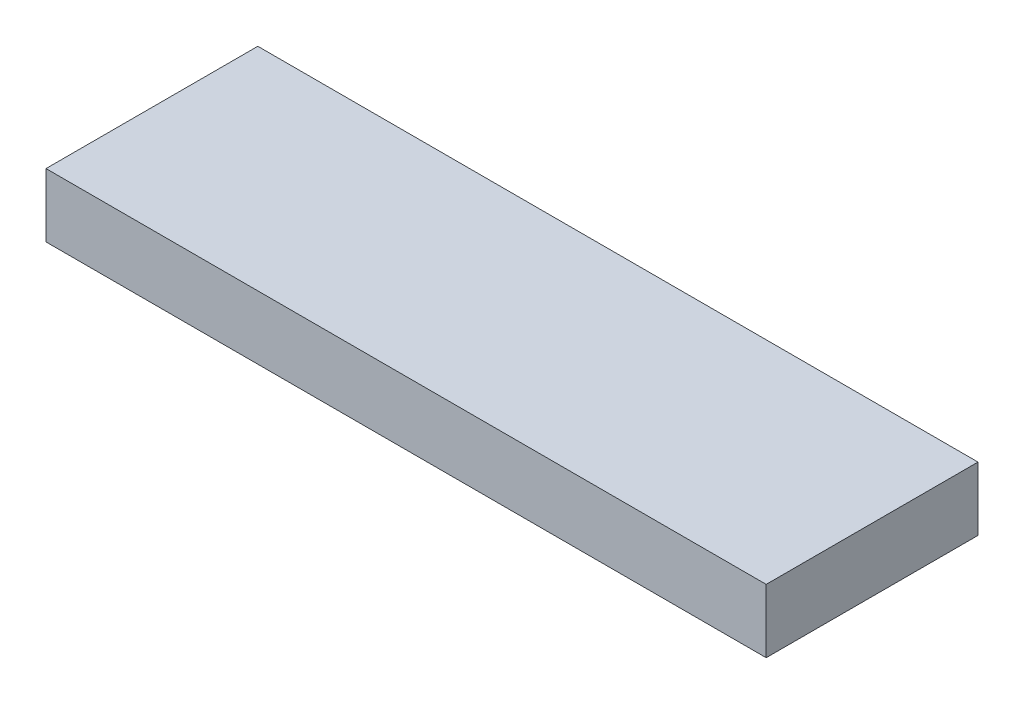
SolidWorks part; units mm, degrees
ref_plane "前视基准面" through (0, 0, 0) normal (0, 0, 1) x (1, 0, 0)
ref_plane "上视基准面" through (0, 0, 0) normal (0, 1, 0) x (1, 0, 0)
ref_plane "右视基准面" through (0, 0, 0) normal (1, 0, 0) x (0, 0, -1)
sketch "草图1" plane through (0, 0, 0) normal (0, 1, 0) x (1, 0, 0)
  line L1 (-17, -5) -> (17, -5)
  line L2 (-17, -5) -> (-17, 5)
  line L3 (-17, 5) -> (17, 5)
  line L4 (17, -5) -> (17, 5)
  line L5 (0, 5) -> (0, -5) construction
  line L6 (-17, 0) -> (17, 0) construction
  point P0 (0, 0)
  dimension "D1" = 34
  dimension "D2" = 10
extrude "凸台-拉伸1" add sketch "草图1" along normal blind 3
